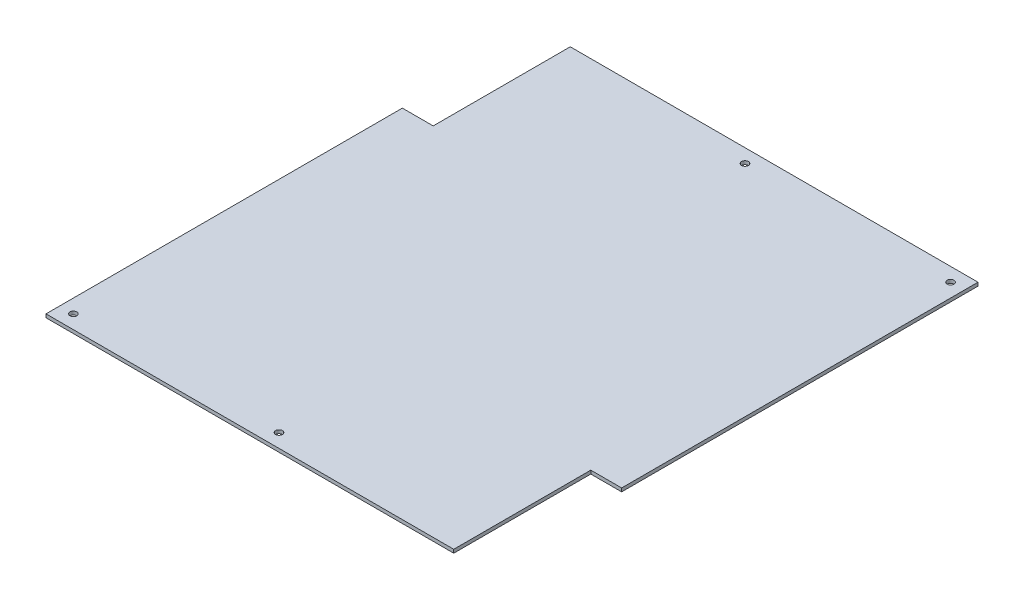
SolidWorks part; units mm, degrees
material "Alloy Steel"
ref_plane "Front" through (0, 0, 0) normal (0, 0, 1) x (1, 0, 0)
ref_plane "Top" through (0, 0, 0) normal (0, 1, 0) x (1, 0, 0)
ref_plane "Right" through (0, 0, 0) normal (1, 0, 0) x (0, 0, -1)
sketch "Sketch1" plane through (0, 0, 0) normal (0, 1, 0) x (1, 0, 0)
  line L1 (203.2, -228.6) -> (-203.2, -228.6)
  line L2 (203.2, -228.6) -> (203.2, 228.6)
  line L3 (203.2, 228.6) -> (-203.2, 228.6)
  line L4 (-203.2, -228.6) -> (-203.2, 228.6)
  line L5 (203.2, -228.6) -> (-203.2, 228.6) construction
  line L6 (203.2, 228.6) -> (-203.2, -228.6) construction
  point P0 (0, 0)
  dimension "D1" = 406.4
  dimension "D2" = 457.2
extrude "Boss-Extrude1" add sketch "Sketch1" along normal blind 3.175
sketch "Sketch2" plane through (0, 3.175, 0) normal (0, 1, 0) x (1, 0, 0)
  line L1 (-203.2, 228.6) -> (-174.625, 228.6)
  line L2 (-203.2, 228.6) -> (-203.2, 101.6)
  line L3 (-203.2, 101.6) -> (-174.625, 101.6)
  line L4 (-174.625, 228.6) -> (-174.625, 101.6)
  line L5 (203.2, -228.6) -> (174.625, -228.6)
  line L6 (203.2, -228.6) -> (203.2, -101.6)
  line L7 (203.2, -101.6) -> (174.625, -101.6)
  line L8 (174.625, -228.6) -> (174.625, -101.6)
  dimension "D1" = 28.575
  dimension "D2" = 127
extrude "Cut-Extrude1" cut sketch "Sketch2" against normal up to next
hole_wizard "1/4 (0.25) Diameter Hole1" positions "Sketch3" profile "Sketch4" hole size "1/4" standard "ANSI Inch" end condition through all
sketch "Sketch3" plane through (0, 3.175, 0) normal (0, 1, 0) x (1, 0, 0)
  line L0 (-203.2, -228.6) -> (174.625, -228.6) construction
  line L1 (-203.2, 101.6) -> (-203.2, -228.6) construction
  line L2 (203.2, 228.6) -> (-174.625, 228.6) construction
  line L3 (203.2, -101.6) -> (203.2, 228.6) construction
  point P0 (-190.5, -215.9)
  point P2 (190.5, 215.9)
  point P4 (0, 215.9)
  point P6 (0, -215.9)
  point P9 (0, 0)
  point P11 (0, 0)
  point P12 (0, 0)
  dimension "D1" = 12.7
  dimension "D2" = 12.7
  dimension "D3" = 12.7
  dimension "D4" = 12.7
sketch "Sketch4" plane through (-190.5, 3.175, 215.9) normal (1, 0, 0) x (0, 0, 1)
  line L0 (0, 0) -> (0, 3.175)
  line L1 (0, 3.175) -> (3.175, 3.175)
  line L2 (3.175, 3.175) -> (3.175, 0)
  line L5 (3.175, 0) -> (0, 0)
  line L11 (0, -6.35) -> (0, 107.95) construction
  dimension "Thru Hole Dia." = 6.35
  dimension "Thru Hole Depth" = 3.175
